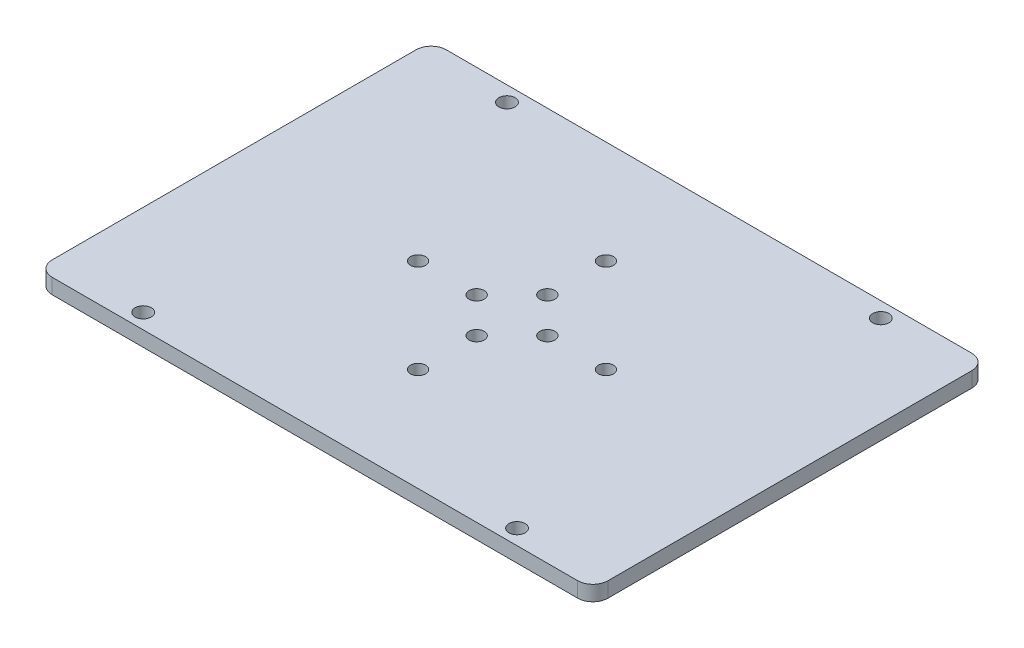
SolidWorks part; units mm, degrees
ref_plane "前视基准面" through (0, 0, 0) normal (0, 0, 1) x (1, 0, 0)
ref_plane "上视基准面" through (0, 0, 0) normal (0, 1, 0) x (1, 0, 0)
ref_plane "右视基准面" through (0, 0, 0) normal (1, 0, 0) x (0, 0, -1)
other "Configuration Table"
sketch "草图1" plane through (0, 0, 0) normal (0, 1, 0) x (1, 0, 0)
  line L0 (-37, -36) -> (37, -36) construction
  line L1 (-37, -36) -> (-37, 36) construction
  line L2 (-37, 36) -> (37, 36) construction
  line L3 (37, -36) -> (37, 36) construction
  line L4 (55, -39) -> (-55, -39)
  line L5 (55, -39) -> (55, 39)
  line L6 (55, 39) -> (-55, 39)
  line L7 (-55, -39) -> (-55, 39)
  line L8 (55, -39) -> (-55, 39) construction
  line L9 (55, 39) -> (-55, -39) construction
  circle A0 centre (-37, 36) radius 1.6
  circle A1 centre (37, 36) radius 1.6
  circle A2 centre (37, -36) radius 1.6
  circle A3 centre (-37, -36) radius 1.6
  point P4 (0, 0)
  point P5 (37, 0)
  point P6 (0, 36)
  point P7 (0, 0)
  dimension "D5" = 3.2
  dimension "D6" = 3.2
  dimension "D7" = 3.2
  dimension "D8" = 3.2
  dimension "D1" = 74
  dimension "D2" = 72
  dimension "D3" = 110
  dimension "D4" = 78
extrude "凸台-拉伸1" add sketch "草图1" along normal blind 3
fillet "圆角1" radius 3 4 edges at (-55, 1.5, -39) (-55, 1.5, 39) (55, 1.5, -39) (55, 1.5, 39)
sketch "草图2" plane through (0, 3, 0) normal (0, 1, 0) x (1, 0, 0)
  line L0 (0, 0) -> (34.7484, 0) construction
  line L1 (0, 0) -> (0, 16.7055) construction
  circle A0 centre (0, 0) radius 7 construction
  circle A1 centre (0, 7) radius 1.5
  circle A2 centre (7, 0) radius 1.5
  circle A3 centre (0, -7) radius 1.5
  circle A4 centre (-7, 0) radius 1.5
  circle A5 centre (18.6, 0) radius 1.5
  circle A6 centre (-18.6, 0) radius 1.5
  circle A7 centre (0, 18.6) radius 1.5
  circle A8 centre (0, -18.6) radius 1.5
  point P14 (0, 0)
  dimension "D1" = 14
  dimension "D2" = 3
  dimension "D4" = 3
  dimension "D6" = 37.2
  dimension "D5" = 37.2
  dimension "D3" = 4
extrude "切除-拉伸1" cut sketch "草图2" against normal blind 10
